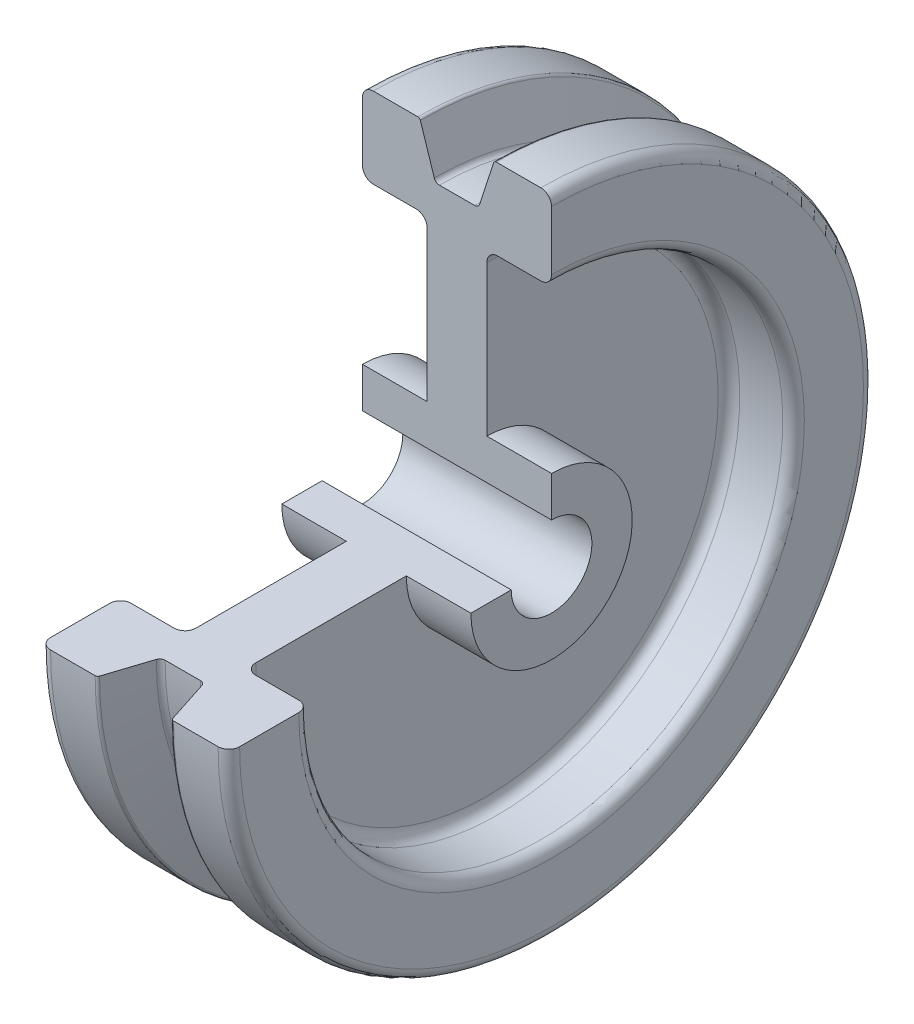
SolidWorks part; units mm, degrees
ref_plane "정면" through (0, 0, 0) normal (0, 0, 1) x (1, 0, 0)
ref_plane "윗면" through (0, 0, 0) normal (0, 1, 0) x (1, 0, 0)
ref_plane "우측면" through (0, 0, 0) normal (1, 0, 0) x (0, 0, -1)
sketch "스케치1" plane through (0, 0, 0) normal (0, 0, 1) x (1, 0, 0)
  line L0 (-22.8146, 0) -> (24.4957, 0) construction
  line L1 (2.8561, 7.5) -> (20.4353, 7.5)
  line L2 (20.4353, 7.5) -> (20.4353, 15)
  line L3 (20.4353, 15) -> (8.4277, 15)
  line L4 (8.4277, 15) -> (8.4277, 45)
  line L5 (8.4277, 45) -> (20.4353, 45)
  line L6 (20.4353, 45) -> (20.4353, 60)
  line L7 (20.4353, 60) -> (9.7804, 60)
  line L8 (9.7804, 60) -> (6.8561, 51)
  line L9 (6.8561, 51) -> (2.8561, 51)
  line L10 (2.8561, 51) -> (2.8561, 7.5)
  point P9 (8.9031, 57.3)
  dimension "D1" = 18
  dimension "D2" = 6.3
  dimension "D3" = 2.7
  dimension "D4" = 4
  dimension "D5" = 15
  dimension "D6" = 30
  dimension "D7" = 90
  dimension "D8" = 120
revolve "회전1" add sketch "스케치1" angle 360 about L0
mirror "대칭 복사2" about plane through (2.8561, 51, 0) normal (1, 0, 0) of "회전1"
fillet "필렛1" radius 0.5 2 edges at (9.7804, 0, 60) (-4.0682, 0, 60)
fillet "필렛2" radius 1 2 edges at (6.8561, 0, 51) (-1.1439, 0, 51)
fillet "필렛3" radius 2 2 edges at (20.4353, 0, 60) (-14.7232, 0, 60)
sketch "스케치2" plane through (20.4353, 0, 0) normal (1, 0, 0) x (0, 0, -1)
  line L1 (-70, 70) -> (0, 70)
  line L2 (-70, 70) -> (-70, 0)
  line L3 (-70, 0) -> (0, 0)
  line L4 (0, 70) -> (0, 0)
  line L5 (-70, 70) -> (0, 0) construction
  line L6 (-70, 0) -> (0, 70) construction
  point P1 (-35, 35)
  point P6 (-104.1067, 81.3667)
  dimension "D1" = 70
  dimension "D2" = 70
extrude "컷-돌출2" cut sketch "스케치2" against normal blind 40 contours L1 L4 L3 L2
fillet "필렛4" radius 2 4 edges at (8.4277, -31.8198, -31.8198) (-2.7155, -31.8198, -31.8198) (-14.7232, -31.8198, -31.8198) (20.4353, -31.8198, -31.8198)
